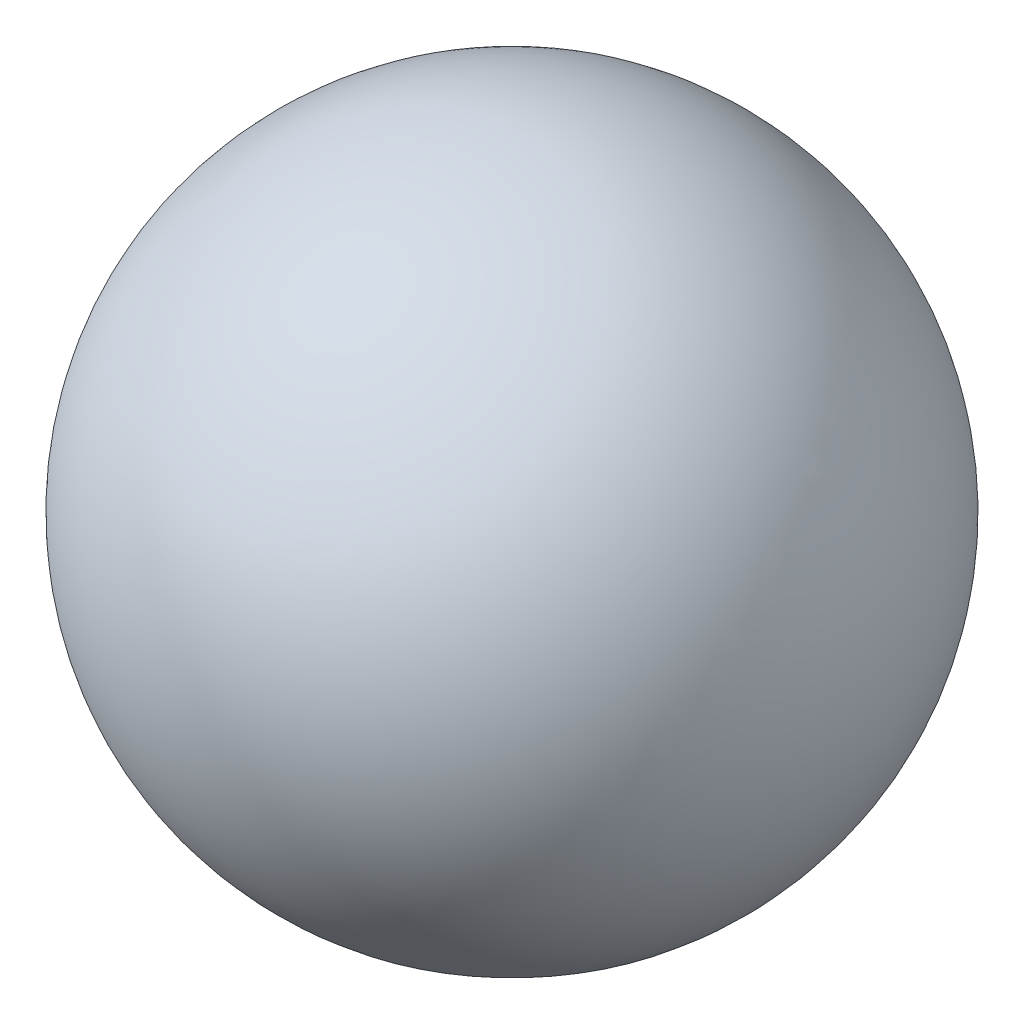
SolidWorks part; units mm, degrees
ref_plane "Plano frontal" through (0, 0, 0) normal (0, 0, 1) x (1, 0, 0)
ref_plane "Plano superior" through (0, 0, 0) normal (0, 1, 0) x (1, 0, 0)
ref_plane "Plano direito" through (0, 0, 0) normal (1, 0, 0) x (0, 0, -1)
sketch "Esboço1" plane through (0, 0, 0) normal (0, 0, 1) x (1, 0, 0)
  line L0 (0, 0) -> (0, 3089) construction
  line L1 (1054.286, 0) -> (1070.5228, 0)
  line L2 (0, 3089) -> (0, 3079)
  arc A0 (0, 3089) -> (1070.5228, 0) centre (0, 1359) cw
  arc A1 (0, 3079) -> (1054.286, 0) centre (0, 1359) cw
  dimension "D2" = 1730
  dimension "D3" = 10
  dimension "D1" = 3089
revolve "Revolução1" add sketch "Esboço1" angle 360 about L0
